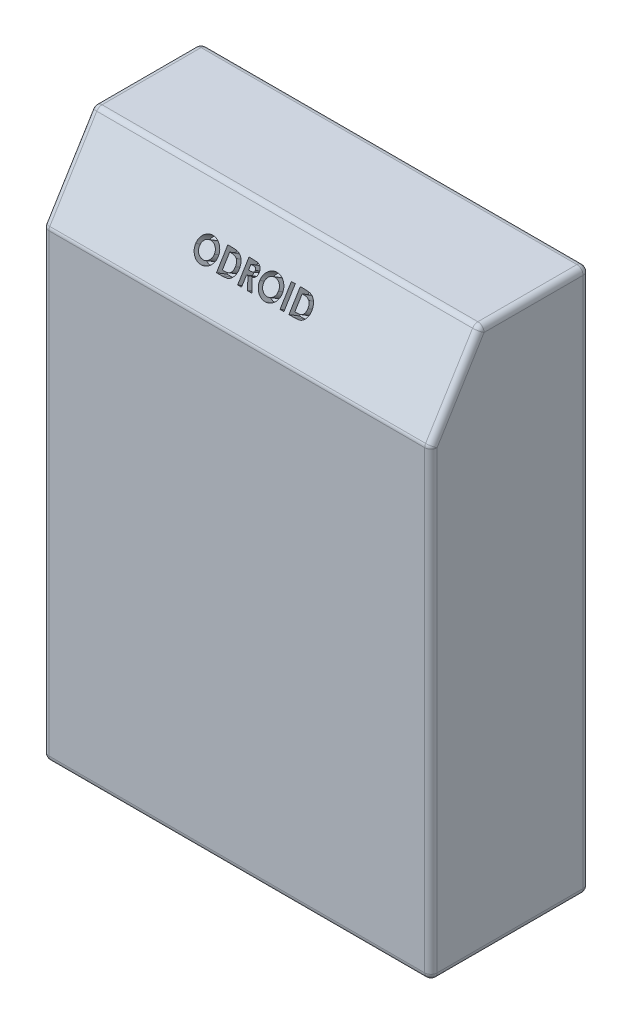
SolidWorks part; units mm, degrees
ref_plane "Front Plane" through (0, 0, 0) normal (0, 0, 1) x (1, 0, 0)
ref_plane "Top Plane" through (0, 0, 0) normal (0, 1, 0) x (1, 0, 0)
ref_plane "Right Plane" through (0, 0, 0) normal (1, 0, 0) x (0, 0, -1)
sketch "Sketch1" plane through (0, 0, 0) normal (0, 0, 1) x (1, 0, 0)
  line L1 (-31.25, -43.75) -> (31.25, -43.75)
  line L2 (-31.25, -43.75) -> (-31.25, 43.75)
  line L3 (-31.25, 43.75) -> (31.25, 43.75)
  line L4 (31.25, -43.75) -> (31.25, 43.75)
  line L5 (-31.25, -43.75) -> (31.25, 43.75) construction
  line L6 (-31.25, 43.75) -> (31.25, -43.75) construction
  point P0 (0, 0)
extrude "Boss-Extrude1" add sketch "Sketch1" along normal blind 25.5
sketch "Sketch2" plane through (31.25, 0, 0) normal (1, 0, 0) x (0, 0, -1)
  line L0 (-25.5, 43.75) -> (-17.5, 43.75)
  line L1 (-25.5, 43.75) -> (0, 43.75) construction
  line L2 (-25.5, 43.75) -> (-25.5, 30.75)
  line L3 (-25.5, -43.75) -> (-25.5, 43.75) construction
  line L4 (-25.5, 30.75) -> (-17.5, 43.75)
extrude "Cut-Extrude1" cut sketch "Sketch2" against normal blind 65.5
fillet "Fillet1" radius 1 15 edges at (-31.25, -43.75, 12.75) (-31.25, 0, 0) (-31.25, 43.75, 8.75) (0, 43.75, 0) (31.25, 43.75, 8.75) (31.25, 0, 0) (31.25, -43.75, 12.75) (0, -43.75, 0) (0, -43.75, 25.5) (31.25, -6.5, 25.5) (31.25, 37.25, 21.5) (-31.25, -6.5, 25.5) (-31.25, 37.25, 21.5) (0, 30.75, 25.5) (0, 43.75, 17.5)
sketch "Sketch3" plane through (0, 19.8283, 32.221) normal (0, 0.5241, 0.8517) x (1, 0, 0)
  text T0 "<b>ODROID</b>"
extrude "Cut-Extrude2" cut sketch "Sketch3" against normal blind 2
